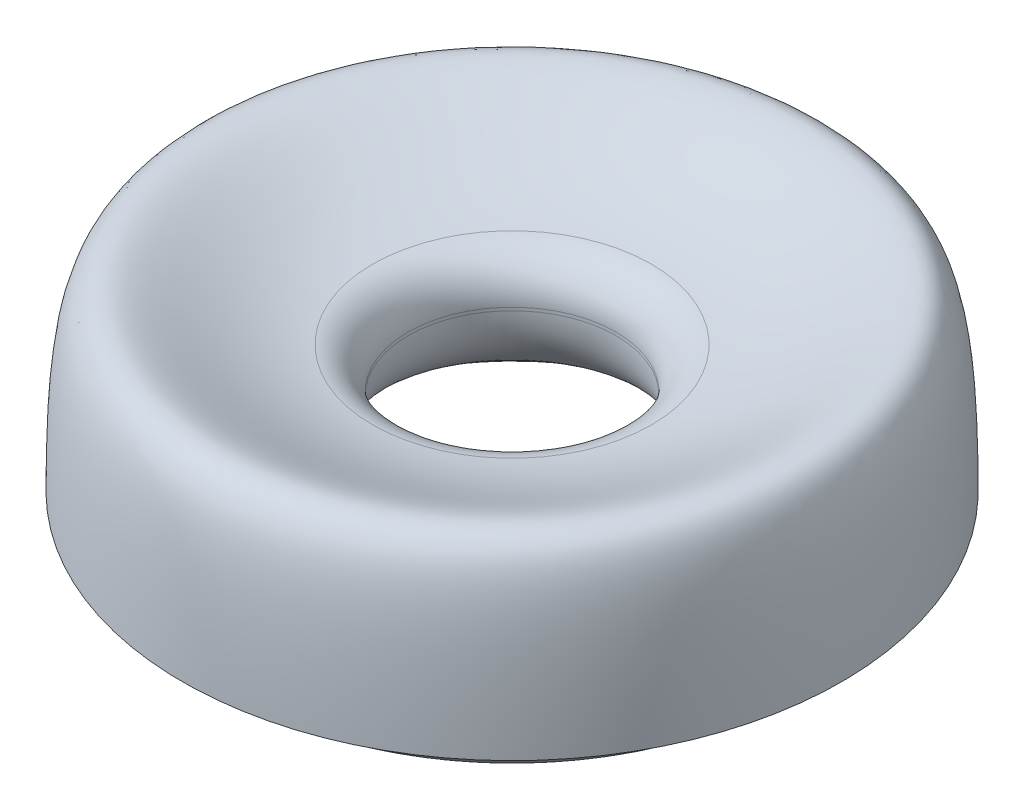
SolidWorks part; units mm, degrees
material "聚脂树脂"
ref_plane "前视基准面" through (0, 0, 0) normal (0, 0, 1) x (1, 0, 0)
ref_plane "上视基准面" through (0, 0, 0) normal (0, 1, 0) x (1, 0, 0)
ref_plane "右视基准面" through (0, 0, 0) normal (1, 0, 0) x (0, 0, -1)
other "Configuration Table"
sketch "草图1" plane through (0, 0, 0) normal (1, 0, 0) x (0, 0, -1)
  line L0 (-6.9282, 112) -> (-7.9282, 112)
  line L1 (-6.9282, 112) -> (-6.9282, 111.5)
  line L2 (-6.4282, 111) -> (-4.9282, 111)
  line L3 (0, 103.1984) -> (0, 120.0027) construction
  line L4 (-7.9282, 112) -> (-7.9282, 119.236) construction
  line L5 (-7.9282, 119.236) -> (-6.5, 115) construction
  line L6 (-6.5, 115) -> (-2.5, 115) construction
  line L7 (-7.9282, 112) -> (-6.9282, 112)
  line L8 (6.9282, 112) -> (7.9342, 112)
  line L9 (-4.9282, 111) -> (-4.9282, 112) construction
  line L10 (-4.9282, 112) -> (-2.5, 112) construction
  line L11 (-2.5, 112) -> (-2.5, 114) construction
  line L12 (-2.5, 114) -> (-2.5, 115)
  line L14 (-7.9282, 112) -> (-6.9282, 112)
  arc A0 (-6.9282, 111.5) -> (-6.4282, 111) centre (-6.4282, 111.5) ccw
  spline S0 degree 3 poles (-7.9282, 112) (-7.9282, 119.236) (-6.5, 115) (-2.5, 115) knots 0 0 0 0 1 1 1 1
  spline S1 degree 3 poles (-4.9282, 111) (-4.9282, 112) (-2.5, 112) (-2.5, 114) knots 0 0 0 0 1 1 1 1
  spline S2 degree 3 poles (-720.4205, -1754.692) (642.9053, 2411.1635) (-472.1585, -2320.2878) (79.4544, 2005.161) knots -2.341328 -2.341328 -2.341328 -2.341328 3.118769 3.118769 3.118769 3.118769 only from (-6.9282, 112) to (-52, 12)
  spline S3 degree 3 poles (-79.7741, 2007.6674) (472.5884, -2322.1091) (-643.1653, 2411.9544) (720.4147, -1754.6743) knots -2.504515 -2.504515 -2.504515 -2.504515 3.630018 3.630018 3.630018 3.630018 only from (44.8632, 14.3881) to (6.9282, 112)
  spline S4 degree 3 poles (44.8632, 14.3881) (25.5616, 26.9052) (6.9282, 85.3813) (6.9282, 112) knots 0 0 0 0 1 1 1 1 construction
  spline S5 degree 3 poles (-6.9282, 112) (-6.9282, 82.0991) (-30.4402, 12) (-52, 12) knots 0 0 0 0 1 1 1 1 construction
  spline S7 degree 3 poles (-79.4623, 2005.2227) (476.6841, -2355.7367) (-661.2769, 2489.2432) (754.3967, -1858.7807) knots -164.603577 -164.603577 -164.603577 -164.603577 263.050795 263.050795 263.050795 263.050795 only from (52, 12) to (51.1665, 12.0346)
  spline S9 degree 3 poles (52, 12) (51.7225, 12) (51.4446, 12.0116) (51.1665, 12.0346) knots 0 0 0 0 1 1 1 1 construction
  point P32 (-6.9282, 111)
  dimension "D2" = 0.5
  dimension "D1" = 1
  dimension "D3" = 2
  dimension "D4" = 1
  dimension "D5" = 4
  dimension "D7" = 4
  dimension "D8" = 2.5
revolve "旋转1" add sketch "草图1" angle 360 about L3
fillet "圆角1" radius 1 2 edges at (0, 115, -2.5) (0, 111, -4.9282)
